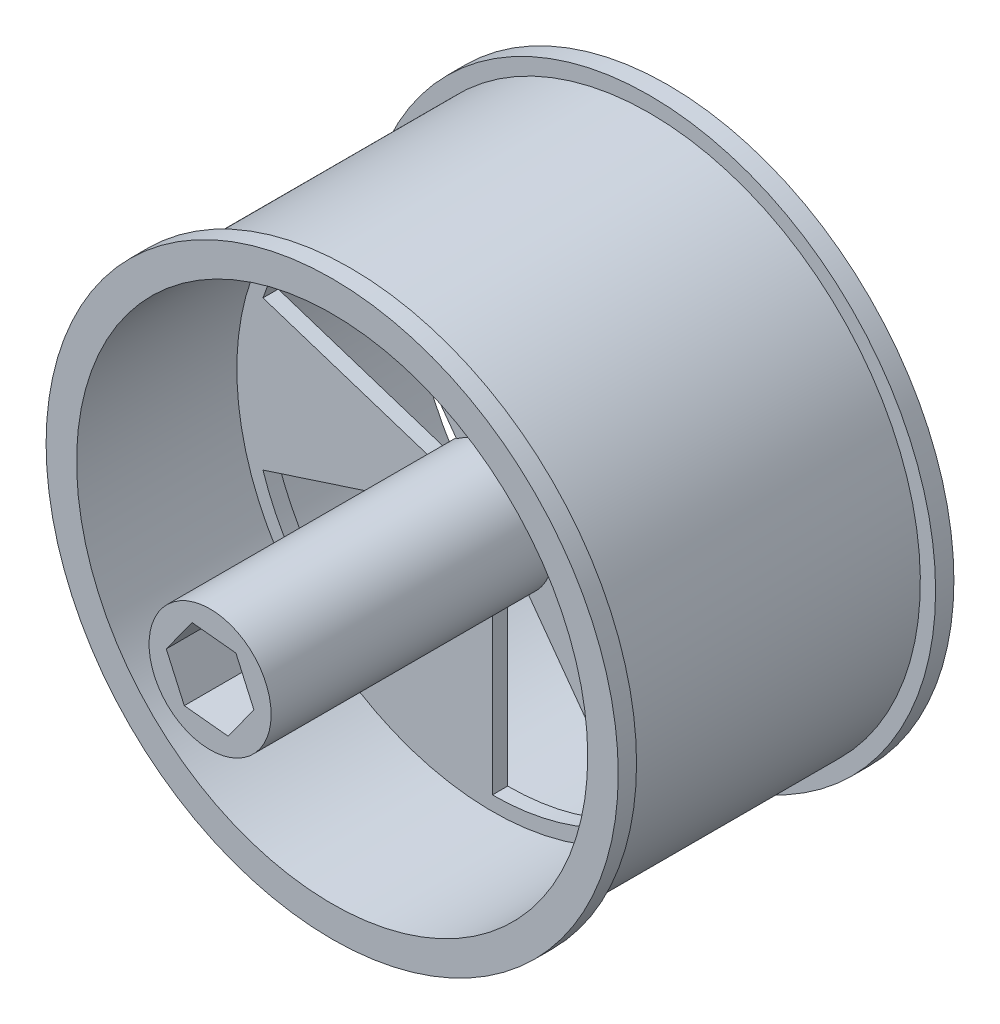
SolidWorks part; units mm, degrees
ref_plane "Front" through (0, 0, 0) normal (0, 0, 1) x (1, 0, 0)
ref_plane "Top" through (0, 0, 0) normal (0, 1, 0) x (1, 0, 0)
ref_plane "Right" through (0, 0, 0) normal (1, 0, 0) x (0, 0, -1)
sketch "Sketch1" plane through (0, 0, 0) normal (0, 0, 1) x (1, 0, 0)
  circle A0 centre (0, 0) radius 23.8125
  circle A1 centre (0, 0) radius 21.2725
  dimension "D1" = 47.625
  dimension "D2" = 2.54
extrude "Boss-Extrude1" add sketch "Sketch1" along normal blind 27.94
sketch "Sketch2" plane through (0, 0, 0) normal (1, 0, 0) x (0, 0, -1)
  line L1 (-1.524, 23.8125) -> (-26.416, 23.8125)
  line L2 (-1.524, 23.8125) -> (-1.524, 22.5425)
  line L3 (-1.524, 22.5425) -> (-26.416, 22.5425)
  line L4 (-26.416, 23.8125) -> (-26.416, 22.5425)
  line L5 (0, 0) -> (-26.416, 0) construction
  line L7 (-27.94, 23.8125) -> (-27.94, -23.8125) construction
  line L8 (0, -23.8125) -> (0, 23.8125) construction
  line L9 (-26.416, 23.8125) -> (-27.94, 23.8125) construction
  dimension "D1" = 1.27
  dimension "D2" = 1.524
  dimension "D3" = 1.524
  dimension "D4" = 23.8125
revolve "Cut-Revolve2" cut sketch "Sketch2" angle 360 about L5
ref_plane "Plane2" through (0, 0, 13.97) normal (0, 0, 1) x (1, 0, 0)
sketch "Sketch5" plane through (0, 0, 13.97) normal (0, 0, 1) x (1, 0, 0)
  circle A0 centre (0, 0) radius 21.2725
  dimension "D1" = 42.545
extrude "Boss-Extrude2" add sketch "Sketch5" along normal mid plane 1.27
sketch "Sketch6" plane through (0, 0, 14.605) normal (0, 0, 1) x (1, 0, 0)
  line L0 (0, 5.08) -> (0, 20.0763)
  line L1 (2.9859, 4.1098) -> (11.8005, 16.2421)
  line L2 (4.8314, 1.5698) -> (19.0937, 6.2039)
  line L3 (4.8314, -1.5698) -> (19.0937, -6.2039)
  line L4 (2.9859, -4.1098) -> (11.8005, -16.2421)
  line L5 (0, -5.08) -> (0, -20.0763)
  line L6 (-2.9859, -4.1098) -> (-11.8005, -16.2421)
  line L7 (-4.8314, -1.5698) -> (-19.0937, -6.2039)
  line L8 (-4.8314, 1.5698) -> (-19.0937, 6.2039)
  line L9 (-2.9859, 4.1098) -> (-11.8005, 16.2421)
  arc A0 (-2.9859, 4.1098) -> (-4.8314, 1.5698) centre (0, 0) ccw
  arc A1 (19.0937, 6.2039) -> (19.0937, -6.2039) centre (0, 0) cw
  arc A2 (0, 20.0763) -> (11.8005, 16.2421) centre (0, 0) cw
  arc A3 (11.8005, -16.2421) -> (0, -20.0763) centre (0, 0) cw
  arc A4 (-11.8005, -16.2421) -> (-19.0937, -6.2039) centre (0, 0) cw
  arc A5 (-19.0937, 6.2039) -> (-11.8005, 16.2421) centre (0, 0) cw
  arc A6 (2.9859, 4.1098) -> (0, 5.08) centre (0, 0) ccw
  arc A7 (4.8314, -1.5698) -> (4.8314, 1.5698) centre (0, 0) ccw
  arc A8 (0, -5.08) -> (2.9859, -4.1098) centre (0, 0) ccw
  arc A9 (-4.8314, -1.5698) -> (-2.9859, -4.1098) centre (0, 0) ccw
  point P27 (0, 0)
  dimension "D1" = 36
  dimension "D2" = 5
  dimension "D3" = 10.16
extrude "Cut-Extrude2" cut sketch "Sketch6" against normal through all both and the other way through all
sketch "Sketch7" plane through (0, 0, 14.605) normal (0, 0, 1) x (1, 0, 0)
  circle A0 centre (0, 0) radius 5.08
  dimension "D1" = 10.16
extrude "Boss-Extrude7" add sketch "Sketch7" along normal offset from surface (23.495 mm away) 10.16 up to face at (23.8125, 0, 27.94) offset beyond the face yes
sketch "Sketch8" plane through (0, 0, 38.1) normal (0, 0, 1) x (1, 0, 0)
  line L1 (-1.4983, 3.346) -> (-3.6469, 0.3755)
  line L2 (-3.6469, 0.3755) -> (-2.1486, -2.9706)
  line L3 (-2.1486, -2.9706) -> (1.4983, -3.346)
  line L4 (1.4983, -3.346) -> (3.6469, -0.3755)
  line L5 (3.6469, -0.3755) -> (2.1486, 2.9706)
  line L6 (2.1486, 2.9706) -> (-1.4983, 3.346)
  circle A0 centre (0, 0) radius 3.175 construction
  dimension "D1" = 6.35
extrude "Cut-Extrude3" cut sketch "Sketch8" against normal blind 19.05
equation "\"D3@Sketch2\"=\"D2@Sketch2\""
